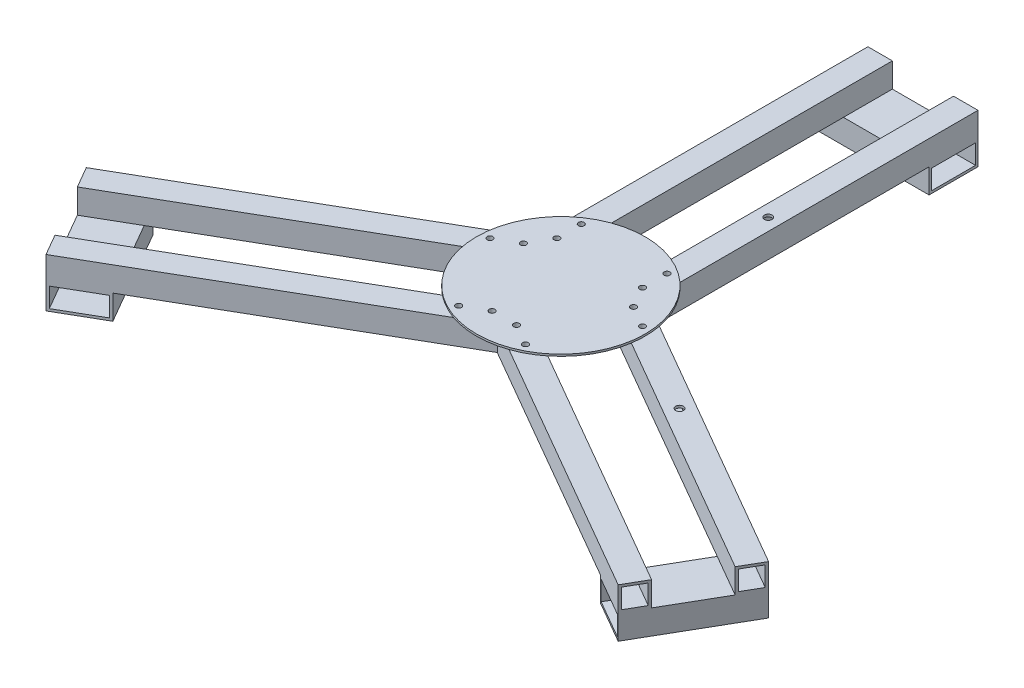
SolidWorks part; units mm, degrees
ref_plane "Front Plane" through (0, 0, 0) normal (0, 0, 1) x (1, 0, 0)
ref_plane "Top Plane" through (0, 0, 0) normal (0, 1, 0) x (1, 0, 0)
ref_plane "Right Plane" through (0, 0, 0) normal (1, 0, 0) x (0, 0, -1)
sketch "Sketch1" plane through (0, 0, 0) normal (0, 1, 0) x (1, 0, 0)
  line L0 (-329.9557, -190.5) -> (0, 0) construction
  line L1 (0, 381) -> (0, 0) construction
  line L2 (0, 0) -> (329.9557, -190.5) construction
  line L3 (-305.4775, -227.6939) -> (22.225, -38.4948) construction
  line L4 (-349.9275, -150.7043) -> (-22.225, 38.4948) construction
  line L5 (-44.45, 378.3982) -> (-44.45, 0) construction
  line L6 (44.45, 378.3982) -> (44.45, 0) construction
  line L9 (-22.225, -38.4948) -> (305.4775, -227.6939) construction
  line L10 (22.225, 38.4948) -> (349.9275, -150.7043) construction
  line L12 (44.45, 381) -> (44.45, 0) construction
  line L13 (-44.45, 381) -> (-44.45, 0) construction
  line L14 (-352.1807, -152.0052) -> (-22.225, 38.4948) construction
  line L15 (-307.7307, -228.9948) -> (22.225, -38.4948) construction
  line L16 (22.225, 38.4948) -> (352.1807, -152.0052) construction
  line L17 (-22.225, -38.4948) -> (307.7307, -228.9948) construction
  circle A0 centre (0, 0) radius 381
  point P15 (323.6057, -201.4985)
  point P17 (336.3057, -179.5015)
  dimension "D1" = 762
  dimension "D2" = 120
  dimension "D3" = 44.45
  dimension "D6" = 44.45
  dimension "D9" = 120
  dimension "D4" = 44.45
  dimension "D5" = 44.45
  dimension "D7" = 44.45
  dimension "D8" = 44.45
ref_plane "Plane2" through (0, 0, -12.7) normal (0, 0, 1) x (1, 0, 0)
sketch "Sketch6" plane through (0, 0, -12.7) normal (0, 0, 1) x (1, 0, 0)
  line L0 (-54.61, 10.16) -> (-34.29, 10.16)
  line L1 (-57.15, -12.7) -> (-31.75, -12.7)
  line L2 (-57.15, -12.7) -> (-57.15, 12.7)
  line L3 (-57.15, 12.7) -> (-31.75, 12.7)
  line L4 (-31.75, -12.7) -> (-31.75, 12.7)
  line L5 (-57.15, -12.7) -> (-31.75, 12.7) construction
  line L6 (-57.15, 12.7) -> (-31.75, -12.7) construction
  line L7 (-34.29, -10.16) -> (-34.29, 10.16)
  line L8 (-54.61, -10.16) -> (-34.29, -10.16)
  line L9 (-54.61, -10.16) -> (-54.61, 10.16)
  line L10 (0, 0) -> (0, 75.873) construction
  line L11 (57.15, 12.7) -> (31.75, -12.7) construction
  line L12 (57.15, -12.7) -> (31.75, 12.7) construction
  line L13 (54.61, -10.16) -> (54.61, 10.16)
  line L14 (54.61, -10.16) -> (34.29, -10.16)
  line L15 (34.29, -10.16) -> (34.29, 10.16)
  line L16 (31.75, -12.7) -> (31.75, 12.7)
  line L17 (57.15, 12.7) -> (31.75, 12.7)
  line L18 (57.15, -12.7) -> (57.15, 12.7)
  line L19 (57.15, -12.7) -> (31.75, -12.7)
  line L20 (54.61, 10.16) -> (34.29, 10.16)
  point P0 (-44.45, 0)
  point P19 (44.45, 0)
  dimension "D1" = 25.4
  dimension "D2" = 25.4
  dimension "D3" = 0
  dimension "D4" = 0
  dimension "D5" = 2.54
extrude "Boss-Extrude3" add sketch "Sketch6" against normal blind 363.22
ref_plane "Plane3" through (-57.15, 0, 0) normal (1, 0, 0) x (0, 0, -1)
sketch "Sketch7" plane through (-57.15, 0, 0) normal (1, 0, 0) x (0, 0, -1)
  line L0 (373.38, -35.5199) -> (327.66, -35.5199)
  line L1 (375.92, -12.7) -> (325.12, -12.7)
  line L2 (375.92, -12.7) -> (375.92, -38.0599)
  line L3 (375.92, -38.0599) -> (325.12, -38.0599)
  line L4 (325.12, -12.7) -> (325.12, -38.0599)
  line L5 (327.66, -15.24) -> (327.66, -35.5199)
  line L6 (373.38, -15.24) -> (327.66, -15.24)
  line L7 (373.38, -15.24) -> (373.38, -35.5199)
  dimension "D1" = 50.8
  dimension "D2" = 25.3599
  dimension "D3" = 2.54
extrude "Boss-Extrude4" add sketch "Sketch7" along normal blind 114.3
sketch "Sketch8" plane through (0, 0, 0) normal (0, 1, 0) x (1, 0, 0)
  line L0 (0, 0) -> (0, 589.3312) construction
sketch "Sketch9" plane through (0, 12.7, 0) normal (0, 1, 0) x (1, 0, 0)
  line L0 (0, 0) -> (-71.5007, 41.2809)
  line L1 (-71.5007, 41.2809) -> (-64.8463, -9.6574)
  line L2 (-64.8463, -9.6574) -> (0, 0)
  line L3 (0, 0) -> (66.1664, 38.2012)
  line L4 (66.1664, 38.2012) -> (56.5317, -13.1953)
  line L5 (56.5317, -13.1953) -> (0, 0)
  line L6 (0, 0) -> (329.9557, -190.5) construction
  line L7 (-329.9557, -190.5) -> (0, 0) construction
  dimension "D1" = 180
  dimension "D2" = 180
extrude "Cut-Extrude1" cut sketch "Sketch9" against normal through all contours L3 L4 L5
sketch "Sketch10" plane through (0, 12.7, 0) normal (0, 1, 0) x (1, 0, 0)
  line L0 (0, 0) -> (-91.3571, 52.7451)
  line L1 (-91.3571, 52.7451) -> (-72.0511, -19.306)
  line L2 (-72.0511, -19.306) -> (0, 0)
  line L3 (0, 0) -> (329.9557, -190.5) construction
  dimension "D1" = 180
extrude "Cut-Extrude2" cut sketch "Sketch10" against normal through all
pattern_circular "CirPattern1" count 3 over 360 about axis through (0, 0, 0) along (0, 1, 0) of bodies 114
sketch "Sketch12" plane through (0, 12.7, 0) normal (0, 1, 0) x (1, 0, 0)
  line L0 (57.15, 375.92) -> (57.15, 32.9956) construction
  line L2 (31.75, 18.3309) -> (57.15, 32.9956) construction
  circle A0 centre (44.45, 40.3279) radius 3
  circle A1 centre (57.15, 18.3309) radius 3
  dimension "D1" = 12.7
  dimension "D3" = 6
  dimension "D2" = 12.7
extrude "Cut-Extrude3" cut sketch "Sketch12" against normal through all
sketch "Sketch13" plane through (0, 12.7, 0) normal (0, 1, 0) x (1, 0, 0)
  circle A0 centre (0, 0) radius 87.5
  dimension "D1" = 175
extrude "Boss-Extrude6" add sketch "Sketch13" along normal blind 2
sketch "Sketch14" plane through (0, -12.7, 0) normal (0, -1, 0) x (1, 0, 0)
  line L0 (0, 0) -> (57.15, -32.9956) construction
  line L1 (57.15, -18.3309) -> (82.398, -3.7539) construction
  line L2 (57.15, -375.92) -> (57.15, -66.258) construction
  line L3 (0, 0) -> (0, 65.9911) construction
  line L4 (0, 0) -> (-57.15, -32.9956) construction
  circle A0 centre (57.15, -18.3309) radius 3
  circle A1 centre (44.45, -40.3279) radius 3
  circle A2 centre (-57.15, -18.3309) radius 3
  circle A3 centre (-44.45, -40.3279) radius 3
  circle A4 centre (12.7, 58.6588) radius 3
  circle A5 centre (-12.7, 58.6588) radius 3
  circle A6 centre (44.45, -65.7279) radius 3
  circle A7 centre (79.147, -5.6309) radius 3
  circle A8 centre (34.697, 71.3588) radius 3
  circle A9 centre (-34.697, 71.3588) radius 3
  circle A10 centre (-79.147, -5.6309) radius 3
  circle A11 centre (-44.45, -65.7279) radius 3
  point P20 (0, 0)
  point P39 (0, 0)
  dimension "D1" = 6
  dimension "D2" = 6
  dimension "D4" = 6
  dimension "D6" = 120
  dimension "D7" = 6
  dimension "D3" = 3
  dimension "D5" = 25.4
  dimension "D8" = 25.4
  dimension "D9" = 3
extrude "Cut-Extrude4" cut sketch "Sketch14" against normal through all
sketch "Sketch15" plane through (0, 12.7, 0) normal (0, 1, 0) x (1, 0, 0)
  line L0 (57.15, 375.92) -> (57.15, 66.258) construction
  line L2 (57.15, 375.92) -> (31.75, 375.92) construction
  circle A0 centre (44.45, 170.92) radius 4
  dimension "D1" = 8
  dimension "D2" = 12.7
  dimension "D3" = 205
extrude "Cut-Extrude5" cut sketch "Sketch15" against normal through all
sketch "Sketch16" plane through (0, 12.7, 0) normal (0, 1, 0) x (1, 0, 0)
  line L0 (341.4313, -160.4637) -> (86.4876, -13.2719) construction
  line L1 (341.4313, -160.4637) -> (354.1313, -138.4666) construction
  circle A0 centre (170.2461, -46.9652) radius 4
  dimension "D1" = 8
  dimension "D2" = 12.7
  dimension "D3" = 205
extrude "Cut-Extrude6" cut sketch "Sketch16" against normal through all
